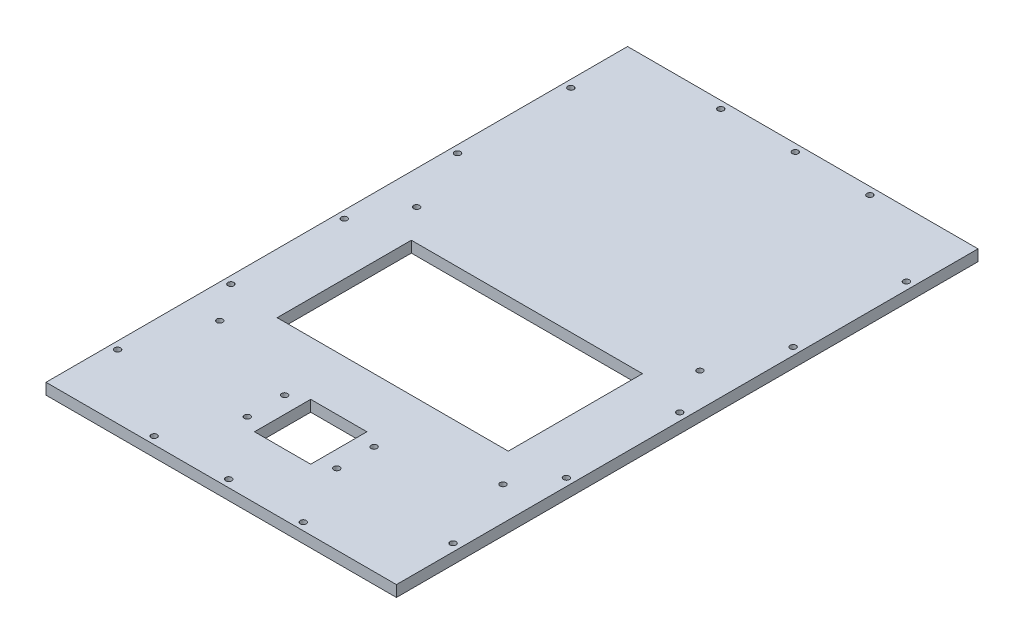
SolidWorks part; units mm, degrees
material "Acrylic (Medium-high impact)"
ref_plane "Front Plane" through (0, 0, 0) normal (0, 0, 1) x (1, 0, 0)
ref_plane "Top Plane" through (0, 0, 0) normal (0, 1, 0) x (1, 0, 0)
ref_plane "Right Plane" through (0, 0, 0) normal (1, 0, 0) x (0, 0, -1)
sketch "Sketch1" plane through (0, 0, 0) normal (0, 1, 0) x (1, 0, 0)
  line L1 (-149.225, -247.65) -> (149.225, -247.65)
  line L2 (-149.225, -247.65) -> (-149.225, 247.65)
  line L3 (-149.225, 247.65) -> (149.225, 247.65)
  line L4 (149.225, -247.65) -> (149.225, 247.65)
  line L5 (-149.225, -247.65) -> (149.225, 247.65) construction
  line L6 (-149.225, 247.65) -> (149.225, -247.65) construction
  line L7 (73.025, -247.65) -> (-130.175, -247.65)
  line L11 (-384.175, -247.65) -> (-231.775, -247.65)
  point P0 (0, 0)
  dimension "D1" = 298.45
  dimension "D2" = 495.3
extrude "Boss-Extrude1" add sketch "Sketch1" along normal mid plane 9.525 contours L1 L4 L3 L2
sketch "Sketch2" [suppressed] plane through (0, 0, 0) normal (0, 1, 0) x (1, 0, 0)
  line L0 (-250.825, -28.575) -> (250.825, -28.575) construction
  line L1 (161.925, -28.575) -> (60.325, -28.575)
  line L2 (161.925, -28.575) -> (161.925, -92.075)
  line L3 (161.925, -92.075) -> (60.325, -92.075)
  line L4 (60.325, -28.575) -> (60.325, -92.075)
  line L5 (0, -5.2388) -> (0, 5.2388) construction
  line L6 (-79.375, -28.575) -> (-168.275, -28.575)
  line L7 (-79.375, -28.575) -> (-79.375, -92.075)
  line L8 (-79.375, -92.075) -> (-168.275, -92.075)
  line L9 (-168.275, -28.575) -> (-168.275, -92.075)
  line L10 (250.825, -28.575) -> (250.825, 28.575) construction
  line L11 (-250.825, -28.575) -> (-250.825, 28.575) construction
  line L12 (-250.825, 28.575) -> (250.825, 28.575) construction
  line L13 (250.825, -28.575) -> (250.825, 28.575) construction
  line L14 (161.925, -28.575) -> (250.825, -28.575)
  line L15 (161.925, -28.575) -> (161.925, -71.755)
  line L16 (161.925, -71.755) -> (250.825, -71.755)
  line L17 (250.825, -28.575) -> (250.825, -71.755)
  line L18 (-250.825, -28.575) -> (-250.825, 28.575) construction
  line L19 (-79.375, -28.575) -> (60.325, -28.575)
  line L20 (-79.375, -28.575) -> (-79.375, -53.975)
  line L21 (-79.375, -53.975) -> (60.325, -53.975)
  line L22 (60.325, -28.575) -> (60.325, -53.975)
  line L23 (-168.275, -28.575) -> (-250.825, -28.575)
  line L24 (-168.275, -28.575) -> (-168.275, -71.755)
  line L25 (-168.275, -71.755) -> (-250.825, -71.755)
  line L26 (-250.825, -28.575) -> (-250.825, -71.755)
  point P19 (60.325, -92.075)
  dimension "D1" = 139.7
  dimension "D2" = 88.9
  dimension "D3" = 82.55
  dimension "D4" = 79.375
  dimension "D5" = 120.65
  dimension "D6" = 43.18
  dimension "D7" = 25.4
  dimension "D8" = 43.18
extrude "Boss-Extrude2" [suppressed] add sketch "Sketch2" along normal mid plane 9.525 contours L6 L9 L8 L7 | L23 L26 L25 L9 | L7 L21 L4 L19 | L17 L14 L2 L16
sketch "Sketch3" plane through (0, 4.7625, 0) normal (0, 1, 0) x (1, 0, 0)
  line L0 (-149.225, 247.65) -> (149.225, 247.65) construction
  line L1 (-98.425, 12.7) -> (98.425, 12.7)
  line L2 (-98.425, 12.7) -> (-98.425, -101.6)
  line L3 (-98.425, -101.6) -> (98.425, -101.6)
  line L4 (98.425, 12.7) -> (98.425, -101.6)
  line L5 (-98.425, 12.7) -> (98.425, -101.6) construction
  line L6 (-98.425, -101.6) -> (98.425, 12.7) construction
  line L7 (-149.225, -247.65) -> (149.225, -247.65) construction
  point P0 (0, -44.45)
  point P7 (0, 247.65)
  point P8 (0, 12.7)
  dimension "D1" = 196.85
  dimension "D2" = 114.3
  dimension "D3" = 203.2
extrude "Cut-Extrude1" cut sketch "Sketch3" against normal through all and the other way through all
sketch "Sketch4" [suppressed] plane through (0, -4.7625, 0) normal (0, -1, 0) x (1, 0, 0)
  line L0 (-107.315, 31.75) -> (107.315, 31.75) construction
  line L1 (-107.315, 33.9979) -> (107.315, 33.9979)
  line L2 (-107.315, 29.5021) -> (107.315, 29.5021)
  line L3 (-107.315, 6.35) -> (107.315, 6.35) construction
  line L4 (-107.315, 8.5979) -> (107.315, 8.5979)
  line L5 (-107.315, 4.1021) -> (107.315, 4.1021)
  arc A0 (-107.315, 33.9979) -> (-107.315, 29.5021) centre (-107.315, 31.75) ccw
  arc A1 (107.315, 29.5021) -> (107.315, 33.9979) centre (107.315, 31.75) ccw
  arc A2 (-107.315, 8.5979) -> (-107.315, 4.1021) centre (-107.315, 6.35) ccw
  arc A3 (107.315, 4.1021) -> (107.315, 8.5979) centre (107.315, 6.35) ccw
  point P0 (-107.315, 31.75)
  point P1 (107.315, 31.75)
  point P3 (107.315, 6.35)
  point P5 (-107.315, 6.35)
  point P10 (0, 31.75)
  point P15 (0, 6.35)
  dimension "D1" = 4.4958
  dimension "D2" = 4.4958
extrude "Cut-Extrude2" [suppressed] cut sketch "Sketch4" against normal through all
sketch "Sketch5" [suppressed] plane through (0, -4.7625, 0) normal (0, -1, 0) x (1, 0, 0)
  line L0 (69.85, 79.375) -> (69.85, -9.525) construction
  line L1 (60.325, 53.975) -> (60.325, 92.075) construction
  line L2 (161.925, 92.075) -> (60.325, 92.075) construction
  line L3 (-247.65, -22.225) -> (247.65, -22.225) construction
  line L4 (69.85, 79.375) -> (69.85, -9.525) construction
  line L5 (72.0979, 79.375) -> (72.0979, -9.525)
  line L6 (67.6021, 79.375) -> (67.6021, -9.525)
  line L7 (-88.9, 79.375) -> (-88.9, -9.525) construction
  line L8 (-79.375, 53.975) -> (-79.375, 92.075) construction
  line L9 (-79.375, 92.075) -> (-168.275, 92.075) construction
  line L10 (-88.9, 79.375) -> (-88.9, -9.525) construction
  line L11 (-86.6521, 79.375) -> (-86.6521, -9.525)
  line L12 (-91.1479, 79.375) -> (-91.1479, -9.525)
  arc A0 (72.0979, 79.375) -> (67.6021, 79.375) centre (69.85, 79.375) ccw
  arc A1 (67.6021, -9.525) -> (72.0979, -9.525) centre (69.85, -9.525) ccw
  arc A2 (-86.6521, 79.375) -> (-91.1479, 79.375) centre (-88.9, 79.375) ccw
  arc A3 (-91.1479, -9.525) -> (-86.6521, -9.525) centre (-88.9, -9.525) ccw
  point P8 (69.85, 34.925)
  point P19 (-88.9, 34.925)
  dimension "D1" = 9.525
  dimension "D2" = 12.7
  dimension "D3" = 12.7
  dimension "D4" = 4.4958
  dimension "D5" = 9.525
  dimension "D6" = 12.7
  dimension "D7" = 12.7
  dimension "D8" = 4.4958
extrude "Cut-Extrude3" [suppressed] cut sketch "Sketch5" against normal through all contours L12 A3 L11 A2 | L6 A1 L5 A0
sketch "Sketch6" [suppressed] plane through (0, 3.175, 0) normal (0, 1, 0) x (1, 0, 0)
  line L0 (-79.375, -38.1) -> (-79.375, 38.1) construction
  line L1 (-88.9, -50.8) -> (-88.9, 50.8) construction
  line L2 (-88.9, -50.8) -> (88.9, -50.8) construction
  line L3 (-88.9, 50.8) -> (88.9, 50.8) construction
  line L4 (79.375, -38.1) -> (79.375, 38.1) construction
  line L5 (88.9, -50.8) -> (88.9, 50.8) construction
  line L6 (-79.375, -38.1) -> (-79.375, 38.1) construction
  line L7 (-81.6229, -38.1) -> (-81.6229, 38.1)
  line L8 (-77.1271, -38.1) -> (-77.1271, 38.1)
  line L9 (79.375, -38.1) -> (79.375, 38.1) construction
  line L10 (77.1271, -38.1) -> (77.1271, 38.1)
  line L11 (81.6229, -38.1) -> (81.6229, 38.1)
  arc A0 (-81.6229, -38.1) -> (-77.1271, -38.1) centre (-79.375, -38.1) ccw
  arc A1 (-77.1271, 38.1) -> (-81.6229, 38.1) centre (-79.375, 38.1) ccw
  arc A2 (77.1271, -38.1) -> (81.6229, -38.1) centre (79.375, -38.1) ccw
  arc A3 (81.6229, 38.1) -> (77.1271, 38.1) centre (79.375, 38.1) ccw
  point P12 (-79.375, 0)
  point P17 (79.375, 0)
  dimension "D1" = 9.525
  dimension "D2" = 12.7
  dimension "D3" = 12.7
  dimension "D4" = 9.525
  dimension "D5" = 12.7
  dimension "D6" = 12.7
  dimension "D7" = 4.4958
  dimension "D8" = 4.4958
extrude "Cut-Extrude4" [suppressed] cut sketch "Sketch6" against normal through all
sketch "Sketch7" [suppressed] plane through (0, 4.7625, 0) normal (0, 1, 0) x (1, 0, 0)
  point P0 (115.1313, 66.802)
  point P1 (139.827, 42.1063)
  point P3 (-139.827, 42.1063)
  point P5 (-115.1313, 66.802)
hole_wizard "#12 Clearance Hole1" [suppressed] positions "Sketch8" profile "Sketch9" hole size "#12" standard "ANSI Inch"
sketch "Sketch8" plane through (0, 4.7625, 0) normal (0, 1, 0) x (1, 0, 0)
  point P0 (-139.827, 42.1063)
  point P3 (-115.1313, 66.802)
  point P6 (115.1313, 66.802)
  point P9 (139.827, 42.1063)
sketch "Sketch9" plane through (-139.827, 4.7625, -42.1063) normal (1, 0, 0) x (0, 0, 1)
  line L0 (0, 0) -> (0, 18.1964)
  line L1 (0, 18.1964) -> (2.8067, 16.51)
  line L2 (2.8067, 16.51) -> (2.8067, 0)
  line L5 (2.8067, 0) -> (0, 0)
  line L10 (0, 18.1964) -> (-2.8067, 16.51) construction
  line L11 (0, -6.35) -> (0, 107.95) construction
  dimension "Hole Dia." = 5.6134
  dimension "Hole Depth" = 16.51
  dimension "Drill Angle" = 118
sketch "Sketch10" [suppressed] plane through (0, -4.7625, 0) normal (0, -1, 0) x (1, 0, 0)
  point P0 (223.8375, -6.35)
  point P1 (223.8375, 19.05)
  point P3 (-223.8375, 19.05)
  point P5 (-223.8375, -6.35)
hole_wizard "#12 Clearance Hole3" [suppressed] positions "Sketch11" profile "Sketch12" hole size "#12" standard "ANSI Inch"
sketch "Sketch11" plane through (0, -4.7625, 0) normal (0, -1, 0) x (-1, 0, 0)
  point P0 (-223.8375, -19.05)
  point P3 (-223.8375, 6.35)
  point P6 (223.8375, -19.05)
  point P9 (223.8375, 6.35)
sketch "Sketch12" plane through (223.8375, -4.7625, 19.05) normal (1, 0, 0) x (0, 0, -1)
  line L0 (0, 0) -> (0, 18.1964)
  line L1 (0, 18.1964) -> (2.8067, 16.51)
  line L2 (2.8067, 16.51) -> (2.8067, 0)
  line L5 (2.8067, 0) -> (0, 0)
  line L10 (0, 18.1964) -> (-2.8067, 16.51) construction
  line L11 (0, -6.35) -> (0, 107.95) construction
  dimension "Hole Dia." = 5.6134
  dimension "Hole Depth" = 16.51
  dimension "Drill Angle" = 118
sketch "Sketch13" [suppressed] plane through (0, -4.7625, 0) normal (0, -1, 0) x (1, 0, 0)
  point P0 (133.35, -223.8375)
  point P1 (107.95, -223.8375)
  point P3 (-107.95, -223.8375)
  point P5 (-133.35, -223.8375)
  point P7 (133.35, 223.8375)
  point P9 (107.95, 223.8375)
  point P11 (-107.95, 223.8375)
  point P13 (-133.35, 223.8375)
hole_wizard "#12 Clearance Hole2" [suppressed] positions "Sketch14" profile "Sketch15" hole size "#12" standard "ANSI Inch"
sketch "Sketch14" [suppressed] plane through (0, -4.7625, 0) normal (0, -1, 0) x (-1, 0, 0)
  point P0 (107.95, -223.8375)
  point P3 (133.35, -223.8375)
  point P6 (133.35, 223.8375)
  point P9 (107.95, 223.8375)
  point P12 (-133.35, 223.8375)
  point P15 (-107.95, 223.8375)
  point P18 (-133.35, -223.8375)
  point P21 (-107.95, -223.8375)
sketch "Sketch15" plane through (-107.95, -4.7625, 223.8375) normal (1, 0, 0) x (0, 0, -1)
  line L0 (0, 0) -> (0, 18.1964)
  line L1 (0, 18.1964) -> (2.8067, 16.51)
  line L2 (2.8067, 16.51) -> (2.8067, 0)
  line L5 (2.8067, 0) -> (0, 0)
  line L10 (0, 18.1964) -> (-2.8067, 16.51) construction
  line L11 (0, -6.35) -> (0, 107.95) construction
  dimension "Hole Dia." = 5.6134
  dimension "Hole Depth" = 16.51
  dimension "Drill Angle" = 118
sketch "Sketch16" [suppressed] plane through (0, 3.175, 0) normal (0, 1, 0) x (1, 0, 0)
  line L0 (88.9, -50.8) -> (88.9, 50.8) construction
  line L1 (-88.9, -50.8) -> (-88.9, 50.8) construction
  line L2 (-88.9, -50.8) -> (88.9, -50.8) construction
  point P0 (79.375, -38.1)
  point P1 (-79.375, -38.1)
  dimension "D1" = 9.525
  dimension "D2" = 9.525
  dimension "D3" = 12.7
hole_wizard "#8 Clearance Hole1" [suppressed] positions "Sketch17" profile "Sketch19" hole size "#8" standard "ANSI Inch"
sketch "Sketch17" plane through (0, 3.175, 0) normal (0, 1, 0) x (1, 0, 0)
  point P0 (79.375, -38.1)
  point P3 (-79.375, -38.1)
sketch "Sketch19" plane through (79.375, 3.175, 38.1) normal (1, 0, 0) x (0, 0, 1)
  line L0 (0, 0) -> (0, 12.0187)
  line L1 (0, 12.0187) -> (2.2479, 10.668)
  line L2 (2.2479, 10.668) -> (2.2479, 0)
  line L5 (2.2479, 0) -> (0, 0)
  line L10 (0, 12.0187) -> (-2.2479, 10.668) construction
  line L11 (0, -6.35) -> (0, 107.95) construction
  dimension "Hole Dia." = 4.4958
  dimension "Hole Depth" = 10.668
  dimension "Drill Angle" = 118
sketch "Sketch20" plane through (0, -4.7625, 0) normal (0, -1, 0) x (1, 0, 0)
  line L0 (-149.225, 247.65) -> (149.225, 247.65) construction
  line L1 (23.9395, 147.5105) -> (-23.9395, 147.5105)
  line L2 (23.9395, 147.5105) -> (23.9395, 195.3895)
  line L3 (23.9395, 195.3895) -> (-23.9395, 195.3895)
  line L4 (-23.9395, 147.5105) -> (-23.9395, 195.3895)
  line L5 (23.9395, 147.5105) -> (-23.9395, 195.3895) construction
  line L6 (23.9395, 195.3895) -> (-23.9395, 147.5105) construction
  line L8 (38.1, 155.575) -> (-38.1, 155.575) construction
  line L9 (38.1, 155.575) -> (38.1, 187.325) construction
  line L10 (38.1, 187.325) -> (-38.1, 187.325) construction
  line L11 (-38.1, 155.575) -> (-38.1, 187.325) construction
  point P0 (0, 171.45)
  point P7 (0, 247.65)
  point P8 (38.1, 155.575)
  point P9 (38.1, 187.325)
  point P10 (-38.1, 155.575)
  point P11 (-38.1, 187.325)
  point P18 (0, 187.325)
  point P19 (0, 195.3895)
  point P20 (-38.1, 171.45)
  point P21 (-23.9395, 171.45)
  dimension "D1" = 47.879
  dimension "D2" = 47.879
  dimension "D3" = 38.1
  dimension "D4" = 15.875
  dimension "D5" = 76.2
extrude "Cut-Extrude5" cut sketch "Sketch20" against normal through all contours L1 L4 L3 L2
hole_wizard "#10 Clearance Hole1" positions "Sketch21" profile "Sketch22" hole size "#10" standard "ANSI Inch"
sketch "Sketch21" plane through (0, -4.7625, 0) normal (0, -1, 0) x (-1, 0, 0)
  point P0 (-38.1, -155.575)
  point P3 (38.1, -155.575)
  point P6 (38.1, -187.325)
  point P9 (-38.1, -187.325)
sketch "Sketch22" plane through (38.1, -4.7625, 155.575) normal (1, 0, 0) x (0, 0, -1)
  line L0 (0, 0) -> (0, 12.2018)
  line L1 (0, 12.2018) -> (2.5527, 10.668)
  line L2 (2.5527, 10.668) -> (2.5527, 0)
  line L5 (2.5527, 0) -> (0, 0)
  line L10 (0, 12.2018) -> (-2.5527, 10.668) construction
  line L11 (0, -6.35) -> (0, 107.95) construction
  dimension "Hole Dia." = 5.1054
  dimension "Hole Depth" = 10.668
  dimension "Drill Angle" = 118
sketch "Sketch23" [suppressed] plane through (-250.825, 0, 0) normal (-1, 0, 0) x (0, 0, 1)
  line L4 (-28.575, -4.7625) -> (71.755, -4.7625)
  line L5 (71.755, -4.7625) -> (71.755, 4.7625)
  line L6 (71.755, 4.7625) -> (-28.575, 4.7625)
  line L7 (-28.575, 4.7625) -> (-28.575, -4.7625)
  line L8 (-28.575, -4.7625) -> (71.755, -4.7625)
  line L9 (71.755, -4.7625) -> (71.755, 4.7625)
  line L10 (71.755, 4.7625) -> (-28.575, 4.7625)
  line L11 (-28.575, 4.7625) -> (-28.575, -4.7625)
  dimension "D1" = 0
extrude "Boss-Extrude3" [suppressed] add sketch "Sketch23" along normal blind 6.35
mirror "Mirror1" [suppressed] about plane through (0, 0, 0) normal (1, 0, 0)
sketch "Sketch27" [suppressed] plane through (0, 4.7625, 0) normal (0, 1, 0) x (1, 0, 0)
  line L1 (257.175, -71.755) -> (257.175, 28.575) construction
  line L2 (-257.175, 28.575) -> (257.175, 28.575) construction
  point P0 (241.3, 12.7)
  dimension "D1" = 15.875
  dimension "D2" = 15.875
hole_wizard "#10 Clearance Hole2" [suppressed] positions "Sketch28" profile "Sketch30" hole size "#10" standard "ANSI Inch"
sketch "Sketch28" plane through (0, 4.7625, 0) normal (0, 1, 0) x (1, 0, 0)
  point P0 (241.3, 12.7)
sketch "Sketch30" plane through (241.3, 4.7625, -12.7) normal (1, 0, 0) x (0, 0, 1)
  line L0 (0, 0) -> (0, 9.525)
  line L1 (0, 9.525) -> (2.5527, 9.525)
  line L2 (2.5527, 9.525) -> (2.5527, 0)
  line L5 (2.5527, 0) -> (0, 0)
  line L11 (0, -6.35) -> (0, 107.95) construction
  dimension "Thru Hole Dia." = 5.1054
  dimension "Thru Hole Depth" = 9.525
pattern_linear "LPattern1" [suppressed] count 6 spacing 96.52
sketch "Sketch31" [suppressed] plane through (0, 4.7625, 0) normal (0, 1, 0) x (1, 0, 0)
  line L1 (0, -5.2388) -> (0, 5.2388) construction
  line L2 (-149.225, 76.2) -> (149.225, 76.2) construction
  point P0 (-95.25, 60.325)
  dimension "D1" = 15.875
  dimension "D2" = 95.25
hole_wizard "#10 Clearance Hole3" [suppressed] positions "Sketch32" profile "Sketch33" hole size "#10" standard "ANSI Inch"
sketch "Sketch32" plane through (0, 4.7625, 0) normal (0, 1, 0) x (1, 0, 0)
  point P0 (-95.25, 60.325)
sketch "Sketch33" plane through (-95.25, 4.7625, -60.325) normal (1, 0, 0) x (0, 0, 1)
  line L0 (0, 0) -> (0, 9.525)
  line L1 (0, 9.525) -> (2.5527, 9.525)
  line L2 (2.5527, 9.525) -> (2.5527, 0)
  line L5 (2.5527, 0) -> (0, 0)
  line L11 (0, -6.35) -> (0, 107.95) construction
  dimension "Thru Hole Dia." = 5.1054
  dimension "Thru Hole Depth" = 9.525
pattern_linear "LPattern2" [suppressed] count 4 spacing 63.5
sketch "Sketch34" plane through (0, 4.7625, 0) normal (0, 1, 0) x (1, 0, 0)
  line L0 (0, -5.2388) -> (0, 5.2388) construction
  line L1 (-149.225, 247.65) -> (149.225, 247.65) construction
  point P0 (-63.5, 241.3)
  dimension "D1" = 63.5
  dimension "D2" = 6.35
hole_wizard "#10 Clearance Hole4" positions "Sketch35" profile "Sketch36" hole size "#10" standard "ANSI Inch" end condition up to next
sketch "Sketch35" plane through (0, 4.7625, 0) normal (0, 1, 0) x (1, 0, 0)
  point P0 (-63.5, 241.3)
sketch "Sketch36" plane through (-63.5, 4.7625, -241.3) normal (1, 0, 0) x (0, 0, 1)
  line L0 (0, 0) -> (0, 9.525)
  line L1 (0, 9.525) -> (2.5527, 9.525)
  line L2 (2.5527, 9.525) -> (2.5527, 0)
  line L5 (2.5527, 0) -> (0, 0)
  line L11 (0, -6.35) -> (0, 107.95) construction
  dimension "Thru Hole Dia." = 5.1054
  dimension "Thru Hole Depth" = 9.525
pattern_linear "LPattern3" count 3 spacing 63.5 along (1, 0, 0) of "#10 Clearance Hole4"
mirror "Mirror2" about plane through (0, 0, 0) normal (0, 0, 1) of "LPattern3", "#10 Clearance Hole4"
sketch "Sketch37" plane through (0, 4.7625, 0) normal (0, 1, 0) x (1, 0, 0)
  line L0 (-5.2388, 0) -> (5.2388, 0) construction
  line L1 (-149.225, -247.65) -> (-149.225, 247.65) construction
  point P0 (-142.875, 0)
  dimension "D1" = 6.35
hole_wizard "#10 Clearance Hole5" positions "Sketch38" profile "Sketch39" hole size "#10" standard "ANSI Inch" end condition up to next
sketch "Sketch38" plane through (0, 4.7625, 0) normal (0, 1, 0) x (1, 0, 0)
  point P0 (-142.875, 0)
sketch "Sketch39" plane through (-142.875, 4.7625, 0) normal (1, 0, 0) x (0, 0, 1)
  line L0 (0, 0) -> (0, 9.525)
  line L1 (0, 9.525) -> (2.5527, 9.525)
  line L2 (2.5527, 9.525) -> (2.5527, 0)
  line L5 (2.5527, 0) -> (0, 0)
  line L11 (0, -6.35) -> (0, 107.95) construction
  dimension "Thru Hole Dia." = 5.1054
  dimension "Thru Hole Depth" = 9.525
pattern_linear "LPattern4" count 3 spacing 96.52 along (0, 0, -1) count 3 spacing 96.52 along (0, 0, 1) of "#10 Clearance Hole5"
mirror "Mirror3" about plane through (0, 0, 0) normal (1, 0, 0) of "LPattern4", "#10 Clearance Hole5"
sketch "Sketch40" [suppressed] plane through (0, 4.7625, 0) normal (0, 1, 0) x (1, 0, 0)
  line L0 (-79.375, -53.975) -> (-79.375, -92.075) construction
  line L3 (-88.9, -79.375) -> (-88.9, -9.525) construction
  line L4 (-91.1479, -79.375) -> (-91.1479, -9.525)
  line L5 (-86.6521, -79.375) -> (-86.6521, -9.525)
  line L6 (69.85, -79.375) -> (69.85, -9.525) construction
  line L7 (67.6021, -79.375) -> (67.6021, -9.525)
  line L8 (72.0979, -79.375) -> (72.0979, -9.525)
  line L9 (60.325, -53.975) -> (60.325, -92.075) construction
  line L12 (-79.375, -92.075) -> (-168.275, -92.075) construction
  line L13 (161.925, -92.075) -> (60.325, -92.075) construction
  arc A2 (-91.1479, -79.375) -> (-86.6521, -79.375) centre (-88.9, -79.375) ccw
  arc A3 (-86.6521, -9.525) -> (-91.1479, -9.525) centre (-88.9, -9.525) ccw
  arc A4 (67.6021, -79.375) -> (72.0979, -79.375) centre (69.85, -79.375) ccw
  arc A5 (72.0979, -9.525) -> (67.6021, -9.525) centre (69.85, -9.525) ccw
  point P7 (-88.9, -44.45)
  point P14 (69.85, -44.45)
  dimension "D1" = 9.525
  dimension "D2" = 4.4958
  dimension "D3" = 4.4958
  dimension "D4" = 9.525
  dimension "D5" = 12.7
  dimension "D6" = 12.7
  dimension "D7" = 69.85
  dimension "D8" = 69.85
extrude "Cut-Extrude6" [suppressed] cut sketch "Sketch40" against normal up to next
sketch "Sketch41" plane through (0, -4.7625, 0) normal (0, -1, 0) x (1, 0, 0)
  point P0 (120.65, -39.4255)
  point P1 (-120.65, -39.4255)
  point P3 (-120.65, 128.3255)
  point P5 (120.65, 128.3255)
hole_wizard "#10 Clearance Hole6" positions "Sketch42" profile "Sketch43" hole size "#10" standard "ANSI Inch" end condition through all
sketch "Sketch42" plane through (0, 4.7625, 0) normal (0, 1, 0) x (1, 0, 0)
  point P0 (120.65, 39.4255)
  point P3 (120.65, -128.3255)
  point P6 (-120.65, -128.3255)
  point P9 (-120.65, 39.4255)
sketch "Sketch43" plane through (120.65, 4.7625, -39.4255) normal (1, 0, 0) x (0, 0, 1)
  line L0 (0, 0) -> (0, 9.525)
  line L1 (0, 9.525) -> (2.5527, 9.525)
  line L2 (2.5527, 9.525) -> (2.5527, 0)
  line L5 (2.5527, 0) -> (0, 0)
  line L11 (0, -6.35) -> (0, 107.95) construction
  dimension "Thru Hole Dia." = 5.1054
  dimension "Thru Hole Depth" = 9.525
